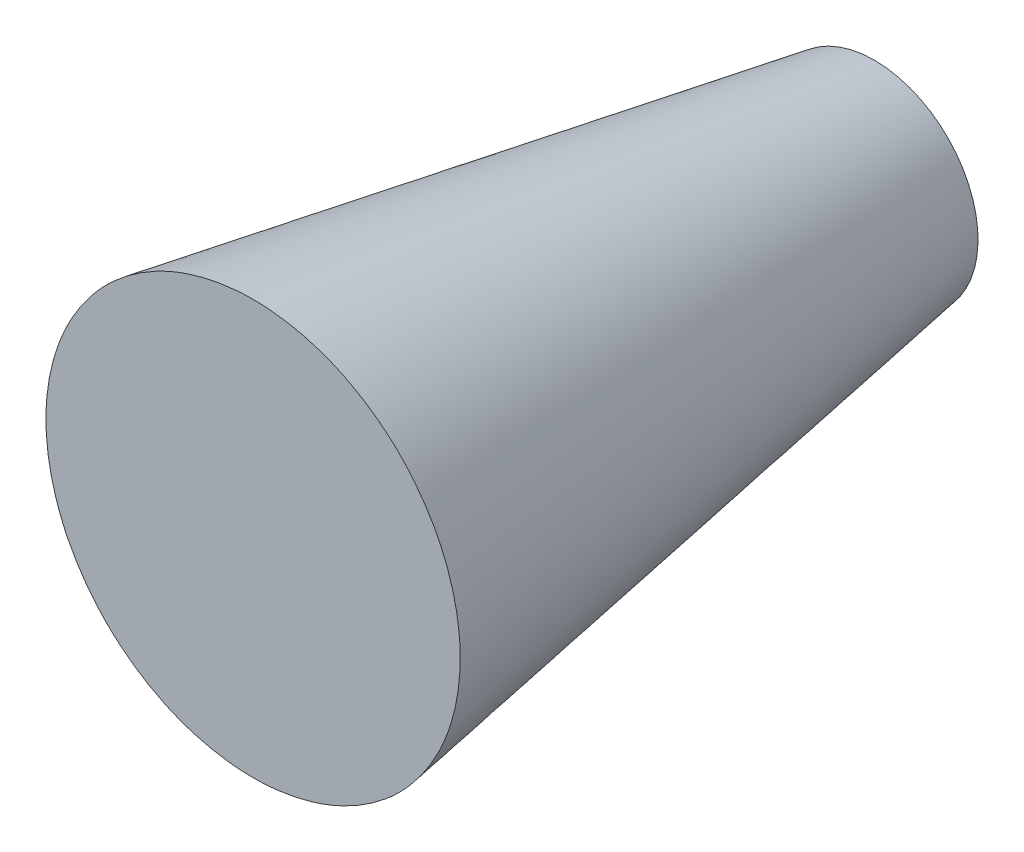
SolidWorks part; units mm, degrees
ref_plane "前视基准面" through (0, 0, 0) normal (0, 0, 1) x (1, 0, 0)
ref_plane "上视基准面" through (0, 0, 0) normal (0, 1, 0) x (1, 0, 0)
ref_plane "右视基准面" through (0, 0, 0) normal (1, 0, 0) x (0, 0, -1)
other "Configuration Table"
sketch "Profile1" plane through (0, 0, 0) normal (0, 0, 1) x (1, 0, 0)
  circle A0 centre (0, 0) radius 5
ref_plane "Plane1" through (0, 0, 15) normal (0, 0, 1) x (1, 0, 0)
sketch "Profile2" plane through (0, 0, 15) normal (0, 0, 1) x (1, 0, 0)
  circle A0 centre (0, 0) radius 7.5
ref_plane "Plane2" through (0, 0, 30) normal (0, 0, 1) x (1, 0, 0)
sketch "Profile3" plane through (0, 0, 30) normal (0, 0, 1) x (1, 0, 0)
  circle A0 centre (0, 0) radius 10
loft "loft_three_sections" add profiles "Profile1", "Profile2", "Profile3"
